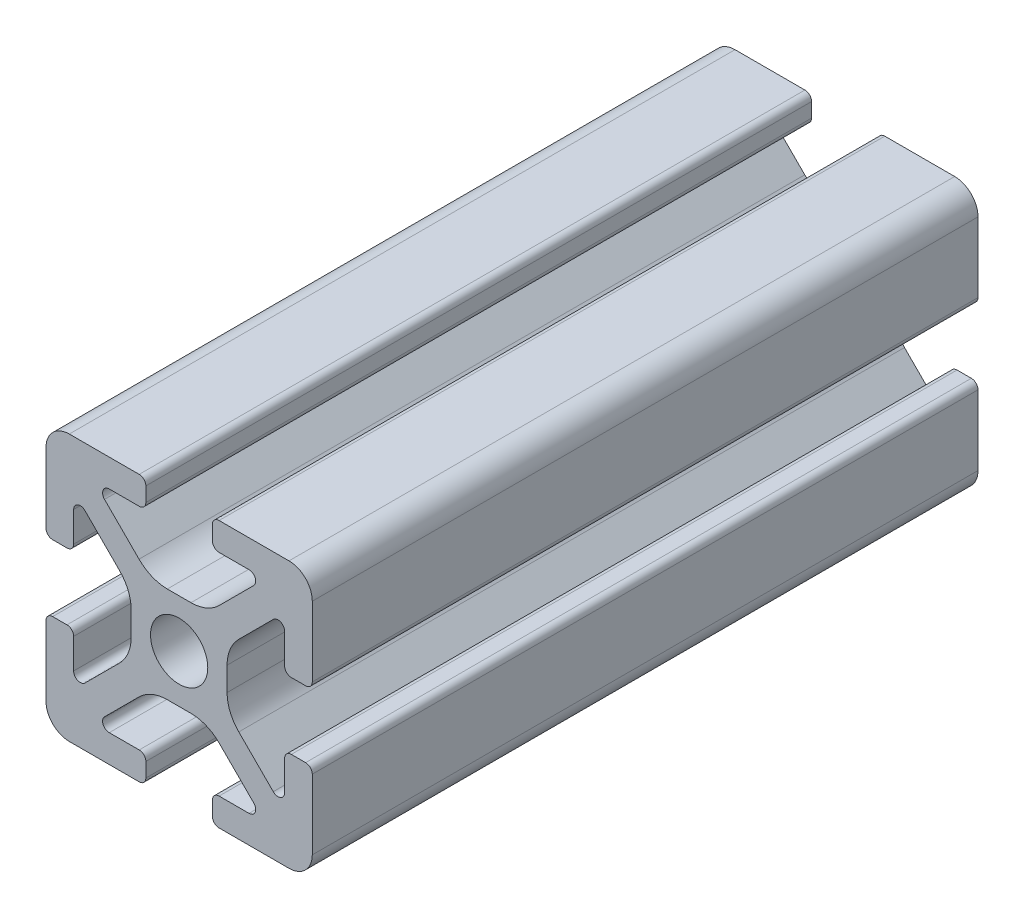
SolidWorks part; units mm, degrees
material "6063-T6"
ref_plane "Front Plane" through (0, 0, 0) normal (0, 0, 1) x (1, 0, 0)
ref_plane "Top Plane" through (0, 0, 0) normal (0, 1, 0) x (1, 0, 0)
ref_plane "Right Plane" through (0, 0, 0) normal (1, 0, 0) x (0, 0, -1)
sketch "Sketch2" plane through (0, 0, 0) normal (0, 0, 1) x (1, 0, 0)
  line L0 (0, 10) -> (0, -10) construction
  line L1 (-10, 0) -> (10, 0) construction
  line L2 (2.5, -10) -> (10, -10)
  line L3 (10, -10) -> (10, -2.5)
  line L4 (2.5, -10) -> (2.5, -7.9246)
  line L5 (2.5, -7.9246) -> (6.4571, -7.9246)
  line L6 (6.4571, -7.9246) -> (2.1325, -3.6)
  line L7 (0, 0) -> (10, -10) construction
  line L8 (10, -2.5) -> (7.9246, -2.5)
  line L9 (7.9246, -2.5) -> (7.9246, -6.4571)
  line L10 (7.9246, -6.4571) -> (3.6, -2.1325)
  line L11 (5.7623, -4.2948) -> (4.2948, -5.7623) construction
  circle A0 centre (0, 0) radius 2.15
  arc A1 (5.25, -7.9246) -> (5.6036, -7.0711) centre (5.25, -7.4246) ccw construction
  point P8 (0, -3.6)
  point P16 (5.0286, -5.0286)
  dimension "Center Hole Diameter" = 4.3
  dimension "D3" = 0.5
  dimension "Rail Height" = 20
  dimension "Rail Width" = 20
  dimension "T-Slot Width" = 5
  dimension "Slot Depth" = 6.4
  dimension "Slot Inner Width" = 11.5
sketch "Sketch3" plane through (0, 0, 0) normal (1, 0, 0) x (0, 0, -1)
  line L0 (-25, -10) -> (25, -10) construction
  line L1 (0.4, 0) -> (-0.4, 0) construction
  line L2 (0, 10) -> (0, -10) construction
  line L3 (0, 10) -> (0, -10) construction
  point P6 (0.4, 0)
  point P8 (-0.4, 0)
  dimension "Length" = 50
  dimension "D1" = 25.4
sketch "Sketch4" plane through (0, 0, 0) normal (0, 0, 1) x (1, 0, 0)
  line L0 (3, -10) -> (8.25, -10)
  line L1 (2.5, -10) -> (10, -10) construction
  line L2 (2.5, -10) -> (2.5, -7.9246) construction
  line L3 (2.5, -7.9246) -> (6.4571, -7.9246) construction
  line L4 (2.5, -8.4246) -> (2.5, -9.5)
  line L5 (3, -7.9246) -> (5.25, -7.9246)
  line L6 (0, -3.6) -> (0.8898, -3.6)
  line L7 (6.4571, -7.9246) -> (2.1325, -3.6) construction
  line L8 (3.0112, -4.4787) -> (5.6036, -7.0711)
  line L9 (10, -10) -> (10, -2.5) construction
  line L10 (7.9246, -6.4571) -> (3.6, -2.1325) construction
  line L11 (7.9246, -2.5) -> (7.9246, -6.4571) construction
  line L12 (7.9246, -5.25) -> (7.9246, -3)
  line L13 (10, -2.5) -> (7.9246, -2.5) construction
  line L14 (8.4246, -2.5) -> (9.5, -2.5)
  line L15 (10, -3) -> (10, -8.25)
  line L16 (7.0711, -5.6036) -> (4.4787, -3.0112)
  line L17 (3.6, 0) -> (3.6, -0.8898)
  line L18 (-10, 0) -> (10, 0) construction
  line L19 (0, -3.6) -> (0, -2.15)
  line L20 (0, 10) -> (0, -10) construction
  line L21 (3.6, 0) -> (2.15, 0)
  arc A0 (2.5, -9.5) -> (3, -10) centre (3, -9.5) ccw
  arc A1 (5.25, -7.9246) -> (5.6036, -7.0711) centre (5.25, -7.4246) ccw construction
  arc A2 (2.5, -8.4246) -> (3, -7.9246) centre (3, -8.4246) cw
  arc A3 (5.25, -7.9246) -> (5.6036, -7.0711) centre (5.25, -7.4246) ccw
  arc A4 (0.8898, -3.6) -> (3.0112, -4.4787) centre (0.8898, -6.6) cw
  arc A5 (8.25, -10) -> (10, -8.25) centre (8.25, -8.25) ccw
  arc A6 (7.0711, -5.6036) -> (7.9246, -5.25) centre (7.4246, -5.25) ccw
  arc A7 (7.9246, -3) -> (8.4246, -2.5) centre (8.4246, -3) cw
  arc A8 (9.5, -2.5) -> (10, -3) centre (9.5, -3) cw
  arc A9 (4.4787, -3.0112) -> (3.6, -0.8898) centre (6.6, -0.8898) cw
  circle A10 centre (0, 0) radius 2.15 construction
  arc A11 (0, -2.15) -> (2.15, 0) centre (0, 0) ccw
  dimension "D1" = 1.75
  dimension "D2" = 3
extrude "Boss-Extrude1" add sketch "Sketch4" along normal mid plane 50
mirror "Mirror1" about plane through (0, 0, 0) normal (1, 0, 0) of bodies 134
mirror "Mirror2" about plane through (0, 0, 0) normal (0, 1, 0) of bodies 135
equation "\"D3@Sketch2\"=\"T-Slot Width@Sketch2\"*0.1"
equation "\"D1@Sketch4\"=\"D3@Sketch2\"*3.5"
equation "\"D2@Sketch4\"=\"D3@Sketch2\"*6"
equation "\"D1@Boss-Extrude1\"=\"Length@Sketch3\""
